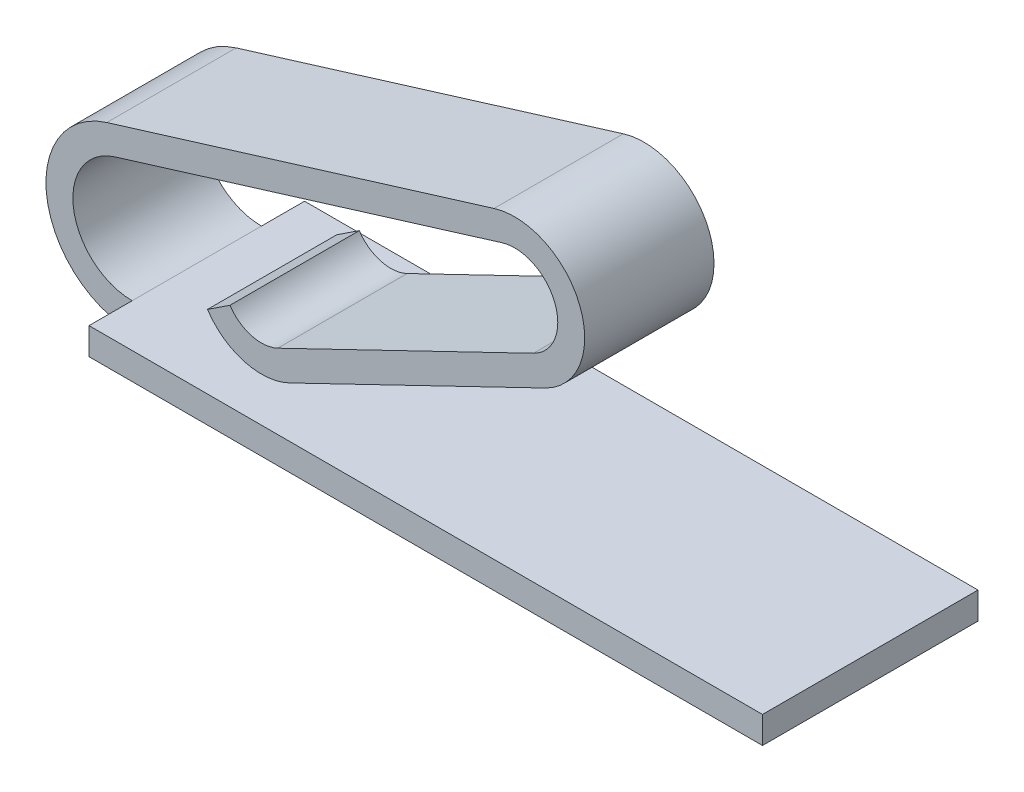
SolidWorks part; units mm, degrees
ref_plane "Front" through (0, 0, 0) normal (0, 0, 1) x (1, 0, 0)
ref_plane "Top" through (0, 0, 0) normal (0, 1, 0) x (1, 0, 0)
ref_plane "Right" through (0, 0, 0) normal (1, 0, 0) x (0, 0, -1)
sketch "Эскиз1" plane through (0, 0, 0) normal (0, 1, 0) x (1, 0, 0)
  line L0 (-3.8459, 0) -> (4.0765, 0) construction
  line L1 (0, 2.2966) -> (0, -2.519) construction
  line L3 (-3.125, 1) -> (3.125, 1)
  line L4 (-3.125, 1) -> (-3.125, -1)
  line L5 (-3.125, -1) -> (3.125, -1)
  line L6 (3.125, 1) -> (3.125, -1)
  point P9 (3.125, 0)
  point P10 (0, 1)
  dimension "D1" = 2
  dimension "D2" = 6.25
extrude "Бобышка-Вытянуть1" add sketch "Эскиз1" along normal blind 0.25
sketch "Эскиз2" plane through (0, 0, 0) normal (0, 0, 1) x (1, 0, 0)
  line L0 (-3.125, 0) -> (3.125, 0) construction
  line L1 (-3.925, 3.0255) -> (-3.925, 0) construction
  line L2 (-3.125, 0) -> (-6.2374, 0) construction
  line L3 (-1.4787, 2.7) -> (2.3044, 2.7) construction
  line L4 (1.075, 4.0907) -> (1.075, 1.4127) construction
  line L5 (-3.3604, 1.5646) -> (0.2337, 2.6712)
  line L6 (-3.125, 0.25) -> (3.125, 0.25) construction
  line L7 (0.7076, 1.4646) -> (-1.6642, 0.3197)
  line L8 (0.5989, 1.6898) -> (-1.7728, 0.5448)
  line L9 (-3.2868, 1.3256) -> (0.3073, 2.4323)
  line L10 (-2.426, 0.5298) -> (-2.2172, 0.6674)
  line L11 (-3.125, 0.25) -> (-3.125, 0)
  line L12 (-3.125, 0.25) -> (-3.125, 0) construction
  arc A0 (-3.125, 0) -> (-3.3604, 1.5646) centre (-3.125, 0.8) cw
  arc A1 (0.2337, 2.6712) -> (0.7076, 1.4646) centre (0.425, 2.05) cw
  arc A2 (-2.426, 0.5298) -> (-1.6642, 0.3197) centre (-1.925, 0.86) ccw
  arc A3 (-2.2172, 0.6674) -> (-1.7728, 0.5448) centre (-1.925, 0.86) ccw
  arc A4 (0.3073, 2.4323) -> (0.5989, 1.6898) centre (0.425, 2.05) cw
  arc A5 (-3.125, 0.25) -> (-3.2868, 1.3256) centre (-3.125, 0.8) cw
  point P24 (0, 0)
  dimension "D1" = 0.8
  dimension "D2" = 0.65
  dimension "D5" = 2
  dimension "D6" = 0.6
  dimension "D7" = 0.61
  dimension "D3" = 2.7
  dimension "D4" = 5
extrude "Бобышка-Вытянуть10" add sketch "Эскиз2" along normal mid plane 1.2
